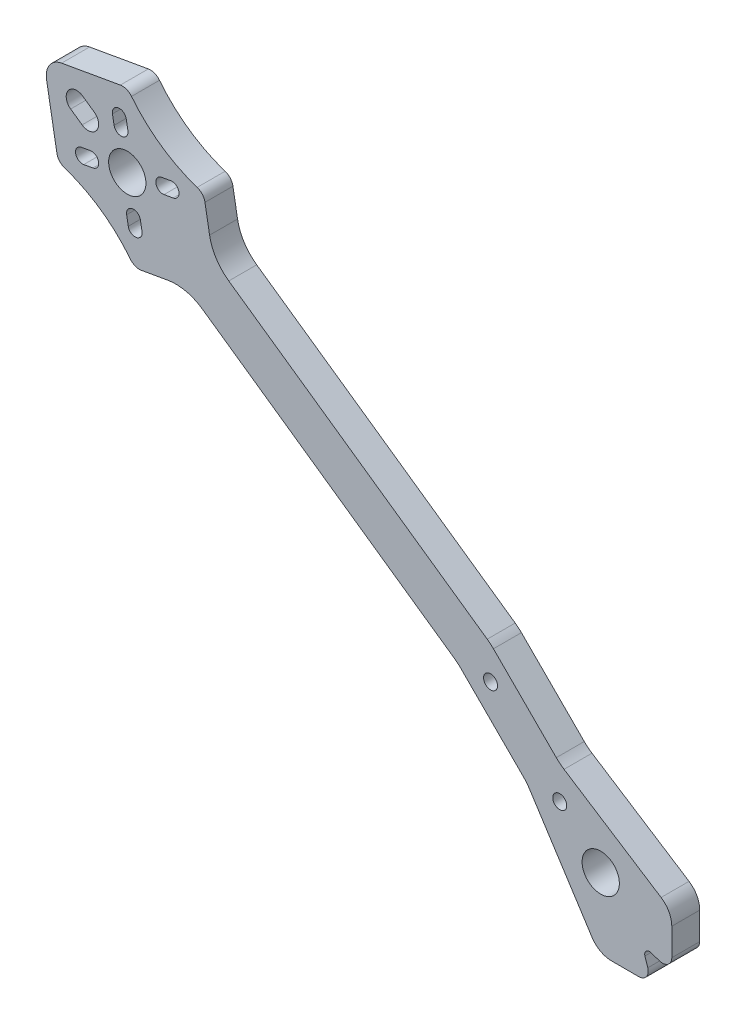
SolidWorks part; units mm, degrees
ref_plane "Alzado" through (0, 0, 0) normal (0, 0, 1) x (1, 0, 0)
ref_plane "Planta" through (0, 0, 0) normal (0, 1, 0) x (1, 0, 0)
ref_plane "Vista lateral" through (0, 0, 0) normal (1, 0, 0) x (0, 0, -1)
sketch "Croquis1" plane through (0, 0, 0) normal (0, 0, 1) x (1, 0, 0)
  line L0 (0, 0) -> (27.8544, 27.8544) construction
  line L1 (0, 0) -> (-42.4264, 42.4264) construction
  line L2 (0, 0) -> (0, 42.4264) construction
  line L3 (15.25, -15.25) -> (-15.25, -15.25) construction
  line L4 (15.25, -15.25) -> (15.25, 15.25) construction
  line L5 (15.25, 15.25) -> (-15.25, 15.25) construction
  line L6 (-15.25, -15.25) -> (-15.25, 15.25) construction
  line L7 (15.25, -15.25) -> (-15.25, 15.25) construction
  line L8 (15.25, 15.25) -> (-15.25, -15.25) construction
  line L9 (0, 42.4264) -> (-20, 42.4264) construction
  line L10 (-42.4264, 42.4264) -> (-38.8909, 45.9619) construction
  line L11 (-38.8909, 45.9619) -> (-31.0962, 38.1673) construction
  line L12 (-20, 42.7635) -> (-20, 80) construction
  line L13 (-42.4264, 42.4264) -> (-45.9619, 38.8909) construction
  line L14 (-45.9619, 38.8909) -> (-38.1673, 31.0962) construction
  line L15 (20, 42.7635) -> (20, 80) construction
  line L16 (38.8909, 45.9619) -> (31.0962, 38.1673) construction
  line L17 (42.4264, 42.4264) -> (38.8909, 45.9619) construction
  line L18 (42.4264, 42.4264) -> (45.9619, 38.8909) construction
  line L19 (-45.9619, -38.8909) -> (-38.1673, -31.0962) construction
  line L20 (0, 0) -> (-15.25, 0) construction
  line L21 (45.9619, 38.8909) -> (38.1673, 31.0962) construction
  line L22 (42.4264, -42.4264) -> (45.9619, -38.8909) construction
  line L23 (42.4264, -42.4264) -> (38.8909, -45.9619) construction
  line L24 (38.8909, -45.9619) -> (31.0962, -38.1673) construction
  line L25 (20, -42.7635) -> (20, -80) construction
  line L26 (-20, -42.7635) -> (-20, -80) construction
  line L27 (-38.8909, -45.9619) -> (-31.0962, -38.1673) construction
  line L28 (-42.4264, -42.4264) -> (-38.8909, -45.9619) construction
  line L29 (-42.4264, -42.4264) -> (-45.9619, -38.8909) construction
  line L30 (45.9619, -38.8909) -> (38.1673, -31.0962) construction
  line L31 (-20, 80) -> (20, 80) construction
  line L32 (0, 80) -> (0, 83) construction
  line L33 (-20, 80) -> (0, 83) construction
  line L34 (0, 83) -> (20, 80) construction
  line L35 (0, -80) -> (0, -83) construction
  line L36 (-20, -80) -> (20, -80) construction
  line L37 (0, -83) -> (20, -80) construction
  line L38 (-20, -80) -> (0, -83) construction
  line L39 (-11, -54) -> (-11, -67.5) construction
  line L41 (-15, -54) -> (-15, -67.5) construction
  line L43 (-13, -54) -> (-13, -67.5) construction
  line L44 (-9, -54) -> (-9, -67.5) construction
  line L45 (-7, -54) -> (-7, -67.5) construction
  line L46 (-5, -54) -> (-5, -67.5) construction
  line L47 (-3, -54) -> (-3, -67.5) construction
  line L48 (-1, -54) -> (-1, -67.5) construction
  line L49 (1, -54) -> (1, -67.5) construction
  line L50 (3, -54) -> (3, -67.5) construction
  line L51 (5, -54) -> (5, -67.5) construction
  line L52 (7, -54) -> (7, -67.5) construction
  line L53 (9, -54) -> (9, -67.5) construction
  line L54 (11, -54) -> (11, -67.5) construction
  line L55 (13, -54) -> (13, -67.5) construction
  line L56 (15, -54) -> (15, -67.5) construction
  line L57 (-11, -35) -> (-11, -48.5) construction
  line L58 (-9, -35) -> (-9, -48.5) construction
  line L59 (-7, -35) -> (-7, -48.5) construction
  line L60 (-5, -35) -> (-5, -48.5) construction
  line L61 (-3, -35) -> (-3, -48.5) construction
  line L62 (-1, -35) -> (-1, -48.5) construction
  line L63 (1, -35) -> (1, -48.5) construction
  line L64 (3, -35) -> (3, -48.5) construction
  line L65 (5, -35) -> (5, -48.5) construction
  line L66 (7, -35) -> (7, -48.5) construction
  line L67 (9, -35) -> (9, -48.5) construction
  line L68 (11, -35) -> (11, -48.5) construction
  line L69 (13, -35) -> (13, -48.5) construction
  line L70 (15, -35) -> (15, -48.5) construction
  line L71 (-15, -35) -> (-15, -48.5) construction
  line L72 (-13, -35) -> (-13, -48.5) construction
  line L73 (-15, 54) -> (-15, 67.5) construction
  line L74 (-13, 35) -> (-13, 48.5) construction
  line L75 (-15, 35) -> (-15, 48.5) construction
  line L76 (15, 35) -> (15, 48.5) construction
  line L77 (13, 35) -> (13, 48.5) construction
  line L78 (11, 35) -> (11, 48.5) construction
  line L79 (9, 35) -> (9, 48.5) construction
  line L80 (7, 35) -> (7, 48.5) construction
  line L81 (5, 35) -> (5, 48.5) construction
  line L82 (3, 35) -> (3, 48.5) construction
  line L83 (1, 35) -> (1, 48.5) construction
  line L84 (-1, 35) -> (-1, 48.5) construction
  line L85 (-3, 35) -> (-3, 48.5) construction
  line L86 (-5, 35) -> (-5, 48.5) construction
  line L87 (-7, 35) -> (-7, 48.5) construction
  line L88 (-9, 35) -> (-9, 48.5) construction
  line L89 (-11, 35) -> (-11, 48.5) construction
  line L90 (15, 54) -> (15, 67.5) construction
  line L91 (13, 54) -> (13, 67.5) construction
  line L92 (11, 54) -> (11, 67.5) construction
  line L93 (9, 54) -> (9, 67.5) construction
  line L94 (7, 54) -> (7, 67.5) construction
  line L95 (5, 54) -> (5, 67.5) construction
  line L96 (3, 54) -> (3, 67.5) construction
  line L97 (1, 54) -> (1, 67.5) construction
  line L98 (-1, 54) -> (-1, 67.5) construction
  line L99 (-3, 54) -> (-3, 67.5) construction
  line L100 (-5, 54) -> (-5, 67.5) construction
  line L101 (-7, 54) -> (-7, 67.5) construction
  line L102 (-9, 54) -> (-9, 67.5) construction
  line L103 (-13, 54) -> (-13, 67.5) construction
  line L104 (-11, 54) -> (-11, 67.5) construction
  line L105 (0, 0) -> (-8.4853, -8.4853) construction
  line L110 (-5.7118, -4.325) -> (-4.3076, -2.2188) construction
  line L111 (-4.325, -5.7118) -> (-2.2188, -4.3076) construction
  line L112 (-4.325, 5.7118) -> (-2.2188, 4.3076) construction
  line L113 (-5.7118, 4.325) -> (-4.3076, 2.2188) construction
  line L114 (5.7118, 4.325) -> (4.3076, 2.2188) construction
  line L115 (4.325, 5.7118) -> (2.2188, 4.3076) construction
  line L116 (4.325, -5.7118) -> (2.2188, -4.3076) construction
  line L117 (5.7118, -4.325) -> (4.3076, -2.2188) construction
  line L123 (-45.9619, 38.8909) -> (-31.0962, 24.0251) construction
  line L124 (-17.1122, 2.2943) -> (-30.516, 23.1236)
  line L125 (-31.8543, 24.7832) -> (-45.9619, 38.8909)
  line L126 (-45.9619, 38.8909) -> (-104.1217, 79.6148)
  line L127 (-31.0962, 24.0251) -> (-24.0251, 31.0962) construction
  line L128 (-38.8909, 45.9619) -> (-24.0251, 31.0962) construction
  line L129 (-2.2943, 17.1122) -> (-23.1236, 30.516)
  line L130 (-24.7832, 31.8543) -> (-38.8909, 45.9619)
  line L131 (-104.1217, 79.6148) -> (-98.4731, 87.6819)
  line L132 (-45.9619, 38.8909) -> (-90.6362, 70.1722) construction
  line L135 (-101.2974, 83.6483) -> (-116.8613, 94.5463) construction
  line L168 (-38.8909, 45.9619) -> (-98.4731, 87.6819)
  line L171 (0, 0) -> (-6.364, 6.364) construction
  line L172 (-5.7629, 4.5039) -> (-5.1526, 2.6149)
  line L173 (-7.0557, 0) -> (-12.9076, 0)
  line L174 (-4.5039, 5.7629) -> (-2.6149, 5.1526)
  line L175 (0, 7.0557) -> (0, 12.9076)
  circle A0 centre (-15.25, 15.25) radius 4 construction
  circle A1 centre (-24.0416, 24.0416) radius 1.5 construction
  circle A2 centre (-38.8909, 38.8909) radius 1.5 construction
  arc A3 (-31.0962, 38.1673) -> (-20, 42.7635) centre (-26.5, 42.7635) ccw construction
  arc A4 (31.0962, 38.1673) -> (20, 42.7635) centre (26.5, 42.7635) cw construction
  circle A5 centre (38.8909, 38.8909) radius 1.5 construction
  circle A6 centre (24.0416, 24.0416) radius 1.5 construction
  circle A7 centre (15.25, 15.25) radius 4 construction
  circle A8 centre (15.25, -15.25) radius 4 construction
  circle A9 centre (24.0416, -24.0416) radius 1.5 construction
  circle A10 centre (38.8909, -38.8909) radius 1.5 construction
  arc A11 (31.0962, -38.1673) -> (20, -42.7635) centre (26.5, -42.7635) ccw construction
  circle A12 centre (-15.25, -15.25) radius 4 construction
  circle A13 centre (-24.0416, -24.0416) radius 1.5 construction
  circle A14 centre (-38.8909, -38.8909) radius 1.5 construction
  arc A15 (-31.0962, -38.1673) -> (-20, -42.7635) centre (-26.5, -42.7635) cw construction
  arc A16 (-38.1673, -31.0962) -> (-38.1673, 31.0962) centre (-69.2635, 0) ccw construction
  arc A17 (38.1673, -31.0962) -> (38.1673, 31.0962) centre (69.2635, 0) cw construction
  circle A18 centre (0, 0) radius 1.5 construction
  circle A19 centre (-16, -75) radius 1.5 construction
  circle A20 centre (-16, -30) radius 1.5 construction
  circle A21 centre (-16, 30) radius 1.5 construction
  circle A22 centre (-16, 75) radius 1.5 construction
  circle A23 centre (16, -75) radius 1.5 construction
  circle A24 centre (16, -30) radius 1.5 construction
  circle A25 centre (16, 30) radius 1.5 construction
  circle A26 centre (16, 75) radius 1.5 construction
  arc A27 (-15, -54) -> (-13, -54) centre (-14, -54) cw construction
  arc A28 (-15, -67.5) -> (-13, -67.5) centre (-14, -67.5) ccw construction
  arc A29 (-11, -54) -> (-9, -54) centre (-10, -54) cw construction
  arc A30 (-11, -67.5) -> (-9, -67.5) centre (-10, -67.5) ccw construction
  arc A31 (-7, -54) -> (-5, -54) centre (-6, -54) cw construction
  arc A32 (-7, -67.5) -> (-5, -67.5) centre (-6, -67.5) ccw construction
  arc A33 (-3, -54) -> (-1, -54) centre (-2, -54) cw construction
  arc A34 (-3, -67.5) -> (-1, -67.5) centre (-2, -67.5) ccw construction
  arc A35 (1, -54) -> (3, -54) centre (2, -54) cw construction
  arc A36 (1, -67.5) -> (3, -67.5) centre (2, -67.5) ccw construction
  arc A37 (5, -54) -> (7, -54) centre (6, -54) cw construction
  arc A38 (5, -67.5) -> (7, -67.5) centre (6, -67.5) ccw construction
  arc A39 (9, -54) -> (11, -54) centre (10, -54) cw construction
  arc A40 (9, -67.5) -> (11, -67.5) centre (10, -67.5) ccw construction
  arc A41 (13, -54) -> (15, -54) centre (14, -54) cw construction
  arc A42 (13, -67.5) -> (15, -67.5) centre (14, -67.5) ccw construction
  arc A43 (-11, -35) -> (-9, -35) centre (-10, -35) cw construction
  arc A44 (-11, -48.5) -> (-9, -48.5) centre (-10, -48.5) ccw construction
  arc A45 (-7, -35) -> (-5, -35) centre (-6, -35) cw construction
  arc A46 (-7, -48.5) -> (-5, -48.5) centre (-6, -48.5) ccw construction
  arc A47 (-3, -35) -> (-1, -35) centre (-2, -35) cw construction
  arc A48 (-3, -48.5) -> (-1, -48.5) centre (-2, -48.5) ccw construction
  arc A49 (1, -35) -> (3, -35) centre (2, -35) cw construction
  arc A50 (1, -48.5) -> (3, -48.5) centre (2, -48.5) ccw construction
  arc A51 (5, -35) -> (7, -35) centre (6, -35) cw construction
  arc A52 (5, -48.5) -> (7, -48.5) centre (6, -48.5) ccw construction
  arc A53 (9, -35) -> (11, -35) centre (10, -35) cw construction
  arc A54 (9, -48.5) -> (11, -48.5) centre (10, -48.5) ccw construction
  arc A55 (13, -35) -> (15, -35) centre (14, -35) cw construction
  arc A56 (13, -48.5) -> (15, -48.5) centre (14, -48.5) ccw construction
  arc A57 (-15, -35) -> (-13, -35) centre (-14, -35) cw construction
  arc A58 (-15, -48.5) -> (-13, -48.5) centre (-14, -48.5) ccw construction
  arc A59 (-15, 48.5) -> (-13, 48.5) centre (-14, 48.5) cw construction
  arc A60 (-15, 35) -> (-13, 35) centre (-14, 35) ccw construction
  arc A61 (13, 48.5) -> (15, 48.5) centre (14, 48.5) cw construction
  arc A62 (13, 35) -> (15, 35) centre (14, 35) ccw construction
  arc A63 (9, 48.5) -> (11, 48.5) centre (10, 48.5) cw construction
  arc A64 (9, 35) -> (11, 35) centre (10, 35) ccw construction
  arc A65 (5, 48.5) -> (7, 48.5) centre (6, 48.5) cw construction
  arc A66 (5, 35) -> (7, 35) centre (6, 35) ccw construction
  arc A67 (1, 48.5) -> (3, 48.5) centre (2, 48.5) cw construction
  arc A68 (1, 35) -> (3, 35) centre (2, 35) ccw construction
  arc A69 (-3, 48.5) -> (-1, 48.5) centre (-2, 48.5) cw construction
  arc A70 (-3, 35) -> (-1, 35) centre (-2, 35) ccw construction
  arc A71 (-7, 48.5) -> (-5, 48.5) centre (-6, 48.5) cw construction
  arc A72 (-7, 35) -> (-5, 35) centre (-6, 35) ccw construction
  arc A73 (-11, 48.5) -> (-9, 48.5) centre (-10, 48.5) cw construction
  arc A74 (-11, 35) -> (-9, 35) centre (-10, 35) ccw construction
  arc A75 (13, 67.5) -> (15, 67.5) centre (14, 67.5) cw construction
  arc A76 (13, 54) -> (15, 54) centre (14, 54) ccw construction
  arc A77 (9, 67.5) -> (11, 67.5) centre (10, 67.5) cw construction
  arc A78 (9, 54) -> (11, 54) centre (10, 54) ccw construction
  arc A79 (5, 67.5) -> (7, 67.5) centre (6, 67.5) cw construction
  arc A80 (5, 54) -> (7, 54) centre (6, 54) ccw construction
  arc A81 (1, 67.5) -> (3, 67.5) centre (2, 67.5) cw construction
  arc A82 (1, 54) -> (3, 54) centre (2, 54) ccw construction
  arc A83 (-3, 67.5) -> (-1, 67.5) centre (-2, 67.5) cw construction
  arc A84 (-3, 54) -> (-1, 54) centre (-2, 54) ccw construction
  arc A85 (-7, 67.5) -> (-5, 67.5) centre (-6, 67.5) cw construction
  arc A86 (-7, 54) -> (-5, 54) centre (-6, 54) ccw construction
  arc A87 (-11, 67.5) -> (-9, 67.5) centre (-10, 67.5) cw construction
  arc A88 (-11, 54) -> (-9, 54) centre (-10, 54) ccw construction
  arc A89 (-15, 67.5) -> (-13, 67.5) centre (-14, 67.5) cw construction
  arc A90 (-15, 54) -> (-13, 54) centre (-14, 54) ccw construction
  arc A91 (-4.325, -5.7118) -> (-5.7118, -4.325) centre (-4.8797, -4.8797) cw construction
  arc A92 (-5.7118, 4.325) -> (-4.325, 5.7118) centre (-4.8797, 4.8797) cw construction
  arc A93 (4.325, 5.7118) -> (5.7118, 4.325) centre (4.8797, 4.8797) cw construction
  arc A94 (5.7118, -4.325) -> (4.325, -5.7118) centre (4.8797, -4.8797) cw construction
  circle A95 centre (0, 0) radius 1.5 construction
  arc A96 (2.2188, -4.3076) -> (-2.2188, -4.3076) centre (0, -7.6358) ccw construction
  arc A97 (4.3076, 2.2188) -> (4.3076, -2.2188) centre (7.6358, 0) ccw construction
  arc A98 (-2.2188, 4.3076) -> (2.2188, 4.3076) centre (0, 7.6358) ccw construction
  arc A99 (-4.3076, 2.2188) -> (-4.3076, -2.2188) centre (-7.6358, 0) cw construction
  circle A102 centre (-38.8909, 38.8909) radius 1.5
  circle A103 centre (-24.0416, 24.0416) radius 1.5
  circle A104 centre (-15.25, 15.25) radius 4
  arc A112 (0, 12.9076) -> (-2.2943, 17.1122) centre (-5, 12.9076) ccw
  arc A113 (-12.9076, 0) -> (-17.1122, 2.2943) centre (-12.9076, 5) cw
  arc A114 (-23.1236, 30.516) -> (-24.7832, 31.8543) centre (-17.7121, 38.9253) cw
  arc A115 (-31.8543, 24.7832) -> (-30.516, 23.1236) centre (-38.9253, 17.7121) cw
  arc A143 (-4.5039, 5.7629) -> (-5.7629, 4.5039) centre (-4.8114, 4.8114) ccw
  arc A144 (-2.6149, 5.1526) -> (0, 7.0557) centre (-2, 7.0557) ccw
  arc A145 (-5.1526, 2.6149) -> (-7.0557, 0) centre (-7.0557, 2) cw
  circle A146 centre (-116.8613, 94.5463) radius 88.5 construction
  point P35 (-34.9935, 42.0646)
  point P37 (44.1942, 40.6586)
  point P45 (44.1942, -40.6586)
  point P61 (-34.9935, -42.0646)
  point P305 (0, 0)
  point P308 (-2.8284, 0)
  point P327 (0, 4.3076)
  point P330 (-4.3076, 0)
  point P338 (0, 15.6358)
  point P341 (-15.6358, 0)
  dimension "D2" = 8
  dimension "D4" = 5
  dimension "D8" = 6.5
  dimension "D10" = 3
  dimension "D11" = 3
  dimension "D13" = 4
  dimension "D15" = 3
  dimension "D16" = 3
  dimension "D18" = 45
  dimension "D26" = 1
  dimension "D28" = 4
  dimension "D29" = 19
  dimension "D31" = 177
  dimension "D32" = 9
  dimension "D33" = 5
  dimension "D34" = 10
  dimension "D39" = 1
  dimension "D40" = 2
  dimension "D30" = 170
  dimension "D1" = 30.5
  dimension "D3" = 60
  dimension "D5" = 21
  dimension "D6" = 20
  dimension "D7" = 5
  dimension "D9" = 5
  dimension "D12" = 80
  dimension "D14" = 5
  dimension "D17" = 4
  dimension "D19" = 2
  dimension "D20" = 13.5
  dimension "D21" = 7.5
  dimension "D22" = 5
  dimension "D25" = 12
  dimension "D36" = 38.4332
  dimension "D23" = 8
  dimension "D24" = 2
  dimension "D27" = 4
extrude "Saliente-Extruir1" add sketch "Croquis1" along normal blind 6
sketch "Croquis4" plane through (0, 0, 6) normal (0, 0, 1) x (1, 0, 0)
  line L2 (-116.8613, 94.5463) -> (-134.8827, 107.165) construction
  line L4 (-98.4731, 87.6819) -> (-100.447, 98.8766)
  line L5 (-100.447, 98.8766) -> (-116.8301, 110.3481)
  line L6 (-116.8301, 110.3481) -> (-134.8827, 107.165)
  line L7 (-104.1217, 79.6148) -> (-98.4731, 87.6819)
  line L9 (-38.8909, 45.9619) -> (-98.4731, 87.6819) construction
  line L11 (-104.1217, 79.6148) -> (-115.3165, 77.6409)
  line L12 (-115.3165, 77.6409) -> (-131.6995, 89.1124)
  line L13 (-131.6995, 89.1124) -> (-134.8827, 107.165)
  circle A0 centre (-116.8613, 94.5463) radius 4
  dimension "D1" = 22
  dimension "D3" = 135
  dimension "D4" = 135
  dimension "D6" = 20
  dimension "D7" = 135
extrude "Saliente-Extruir3" add sketch "Croquis4" against normal up to vertex (6 mm away) up to point (-104.1217, 79.6148, 0)
sketch "Croquis5" plane through (0, 0, 6) normal (0, 0, 1) x (1, 0, 0)
  line L0 (-116.8613, 94.5463) -> (-134.8827, 107.165) construction
  line L2 (-129.0056, 100.3031) -> (-126.5482, 98.5824)
  line L4 (-123.9671, 102.2685) -> (-126.4245, 103.9893)
  line L6 (-120.1379, 96.8406) -> (-123.4145, 99.1349) construction
  line L7 (-116.8613, 94.5463) -> (-79.3435, 101.1617) construction
  line L8 (-116.9928, 86.6536) -> (-116.6455, 84.6839)
  line L9 (-108.9686, 94.4149) -> (-106.999, 94.7621)
  line L11 (-109.4895, 97.3693) -> (-107.5199, 97.7166)
  line L13 (-114.0383, 87.1745) -> (-113.691, 85.2049)
  line L14 (-124.754, 94.6777) -> (-126.7237, 94.3304)
  line L15 (-124.2331, 91.7233) -> (-126.2027, 91.376)
  line L16 (-116.7299, 102.439) -> (-117.0772, 104.4086)
  line L17 (-119.6843, 101.9181) -> (-120.0316, 103.8877)
  arc A0 (-129.0056, 100.3031) -> (-126.4245, 103.9893) centre (-127.7151, 102.1462) cw
  arc A1 (-126.5482, 98.5824) -> (-123.9671, 102.2685) centre (-125.2576, 100.4254) ccw
  circle A2 centre (-116.8613, 94.5463) radius 4 construction
  arc A3 (-107.5199, 97.7166) -> (-106.999, 94.7621) centre (-107.2594, 96.2394) cw
  arc A4 (-108.9686, 94.4149) -> (-109.4895, 97.3693) centre (-109.2291, 95.8921) cw
  arc A5 (-113.691, 85.2049) -> (-116.6455, 84.6839) centre (-115.1682, 84.9444) cw
  arc A6 (-116.9928, 86.6536) -> (-114.0383, 87.1745) centre (-115.5155, 86.914) cw
  arc A7 (-126.2027, 91.376) -> (-126.7237, 94.3304) centre (-126.4632, 92.8532) cw
  arc A8 (-124.754, 94.6777) -> (-124.2331, 91.7233) centre (-124.4936, 93.2005) cw
  arc A9 (-120.0316, 103.8877) -> (-117.0772, 104.4086) centre (-118.5544, 104.1482) cw
  arc A10 (-116.7299, 102.439) -> (-119.6843, 101.9181) centre (-118.2071, 102.1785) cw
  circle A11 centre (-116.8613, 94.5463) radius 9.75 construction
  point P23 (-110.7063, 95.6316)
  point P43 (-116.8613, 94.5463)
  dimension "D10" = 135
  dimension "D1" = 3
  dimension "D2" = 4
  dimension "D3" = 4.5
  dimension "D4" = 2.25
  dimension "D5" = 3
  dimension "D6" = 1.5
  dimension "D7" = 2
  dimension "D8" = 6.25
  dimension "D9" = 4
extrude "Cortar-Extruir1" cut sketch "Croquis5" against normal up to vertex (6 mm away)
fillet "Redondeo3" radius 4 1 edges at (-134.8827, 107.165, 3)
sketch "Croquis7" plane through (0, 0, 6) normal (0, 0, 1) x (1, 0, 0)
  line L0 (-131.6995, 89.1124) -> (-115.3165, 77.6409)
  line L1 (-104.1217, 79.6148) -> (-45.9619, 38.8909) construction
  line L3 (-116.8613, 94.5463) -> (-64.7921, 58.087) construction
  line L4 (-116.8301, 110.3481) -> (-100.447, 98.8766)
  arc A0 (-131.6995, 89.1124) -> (-115.3165, 77.6409) centre (-139.7312, 60.2075) cw
  arc A1 (-116.8301, 110.3481) -> (-100.447, 98.8766) centre (-92.4154, 127.7815) ccw
  dimension "D1" = 30
extrude "Cortar-Extruir2" cut sketch "Croquis7" against normal up to vertex (6 mm away)
fillet "Redondeo4" radius 2.5 4 edges at (-116.8301, 110.3481, 3) (-100.447, 98.8766, 3) (-115.3165, 77.6409, 3) (-131.6995, 89.1124, 3)
fillet "Redondeo6" radius 10 4 edges at (-98.4731, 87.6819, 3) (-104.1217, 79.6148, 3) (-38.8909, 45.9619, 3) (-45.9619, 38.8909, 3)
